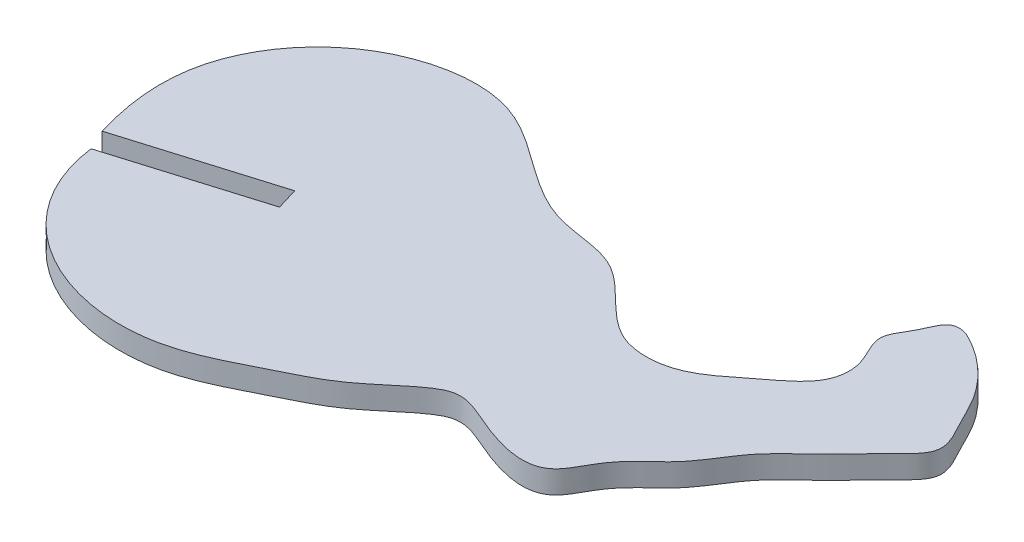
SolidWorks part; units mm, degrees
ref_plane "Спереди" through (0, 0, 0) normal (0, 0, 1) x (1, 0, 0)
ref_plane "Сверху" through (0, 0, 0) normal (0, 1, 0) x (1, 0, 0)
ref_plane "Справа" through (0, 0, 0) normal (1, 0, 0) x (0, 0, -1)
sketch "Эскиз1" plane through (0, 0, 0) normal (0, 1, 0) x (1, 0, 0)
  line L0 (67.558, 140.4457) -> (334.2247, 140.4457) construction
  line L18 (247.7418, 47.8749) -> (273.7861, 55.7296)
  line L26 (273.7861, 55.7296) -> (274.9411, 51.9)
  line L27 (274.9411, 51.9) -> (249.4457, 44.2108)
  spline S6 degree 3 poles (354.7588, 92.9555) (358.9167, 91.0218) (364.3476, 86.2281) (367.7302, 78.6687) (371.3057, 72.7294) (365.5893, 67.6634) (360.7826, 62.0752) (353.8186, 56.3474) (349.501, 47.8023) (342.5279, 43.0048) (338.4667, 32.4978) (327.1668, 36.2207) (319.3523, 40.044) (313.0751, 35.8723) (307.5421, 30.4443) (297.4569, 25.6955) (276.5991, 14.4863) (251.9328, 25.6037) (249.4457, 44.2108) knots 0 0 0 0 0.078227 0.111117 0.144607 0.176641 0.220999 0.274641 0.323696 0.37744 0.41471 0.49024 0.528817 0.552955 0.607499 0.661116 0.737272 1 1 1 1
  spline S7 degree 3 poles (354.7588, 92.9555) (351.2646, 94.2312) (350.6234, 89.7752) (346.4617, 84.7136) (350.2052, 79.9596) (350.1361, 72.7633) (342.567, 67.6241) (335.5166, 61.2582) (322.159, 60.966) (315.1981, 73.9131) (296.0706, 73.7269) (282.3616, 91.269) (256.7767, 85.8007) (244.0635, 67.4712) (245.8768, 54.0589) (247.7418, 47.8749) knots 0 0 0 0 0.042963 0.070836 0.107604 0.135122 0.193651 0.25776 0.308073 0.411831 0.47824 0.630859 0.762731 0.887118 1 1 1 1
  dimension "D1" = 4
extrude "Бобышка-Вытянуть1" add sketch "Эскиз1" along normal blind 4
